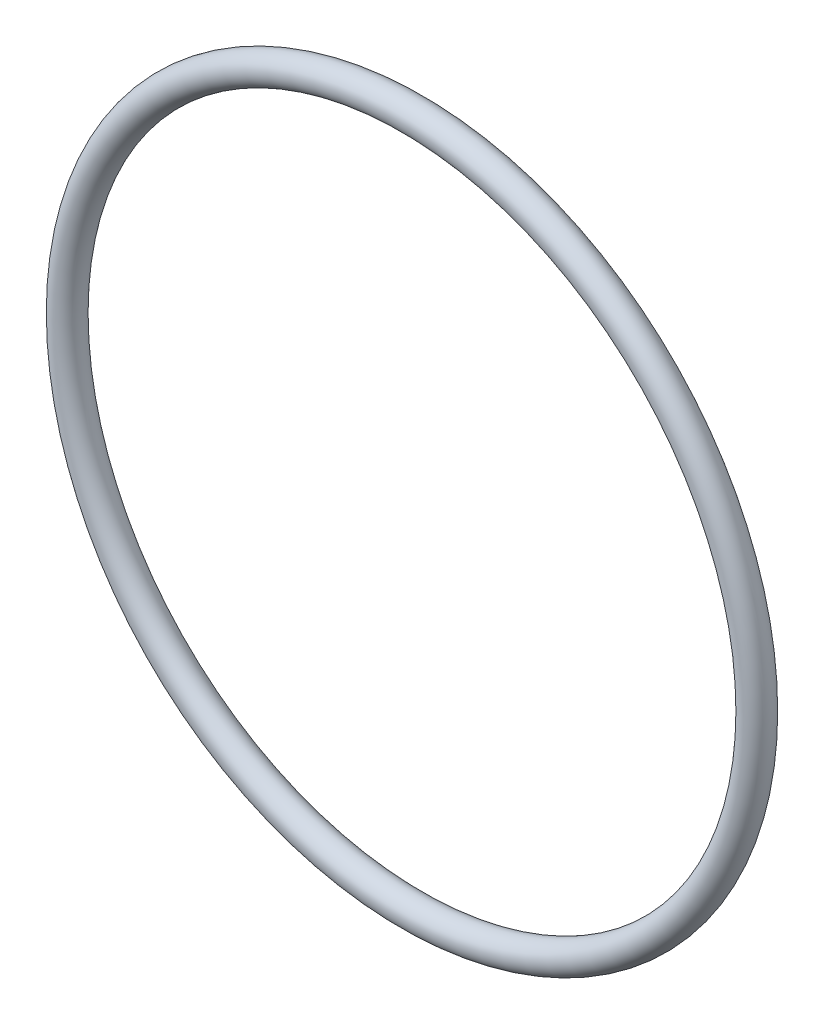
SolidWorks part; units mm, degrees
material "Silicon Rubber"
ref_plane "Front" through (0, 0, 0) normal (0, 0, 1) x (1, 0, 0)
ref_plane "Top" through (0, 0, 0) normal (0, 1, 0) x (1, 0, 0)
ref_plane "Right" through (0, 0, 0) normal (1, 0, 0) x (0, 0, -1)
sketch "Sketch1" plane through (0, 0, 0) normal (1, 0, 0) x (0, -1, 0)
  line L0 (0, -1.3081) -> (0, 1.3081) construction
  line L2 (-35.0088, 0) -> (35.0088, 0) construction
  line L3 (-29.21, 0) -> (29.21, 0) construction
  circle A0 centre (30.5181, 0) radius 1.3081
  point P9 (29.21, 0)
  point P10 (31.8262, 0)
  point P13 (30.5181, 1.3081)
  point P14 (30.5181, -1.3081)
  dimension "Width" = 2.6162
  dimension "ID" = 58.42
revolve "Revolve1" add sketch "Sketch1" angle 360 about L0
